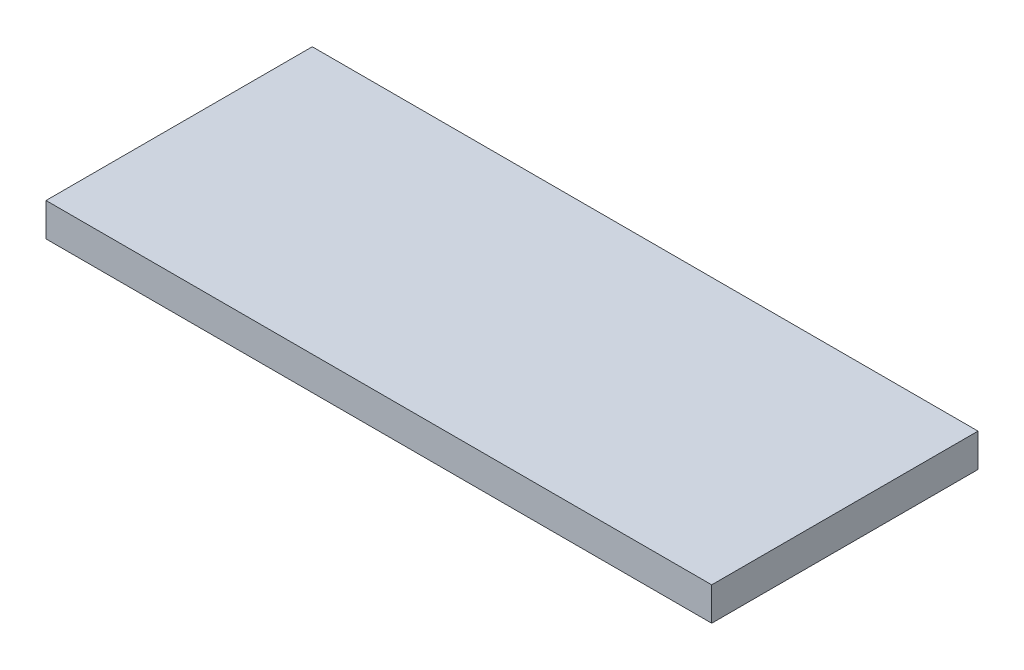
SolidWorks part; units mm, degrees
material "6061 Alloy"
ref_plane "Front Plane" through (0, 0, 0) normal (0, 0, 1) x (1, 0, 0)
ref_plane "Top Plane" through (0, 0, 0) normal (0, 1, 0) x (1, 0, 0)
ref_plane "Right Plane" through (0, 0, 0) normal (1, 0, 0) x (0, 0, -1)
sketch "Sketch1" plane through (0, 0, 0) normal (0, 1, 0) x (1, 0, 0)
  line L1 (0, 0) -> (63.5, 0)
  line L2 (0, 0) -> (0, -25.4)
  line L3 (0, -25.4) -> (63.5, -25.4)
  line L4 (63.5, 0) -> (63.5, -25.4)
extrude "Boss-Extrude1" add sketch "Sketch1" along normal blind 3.175
